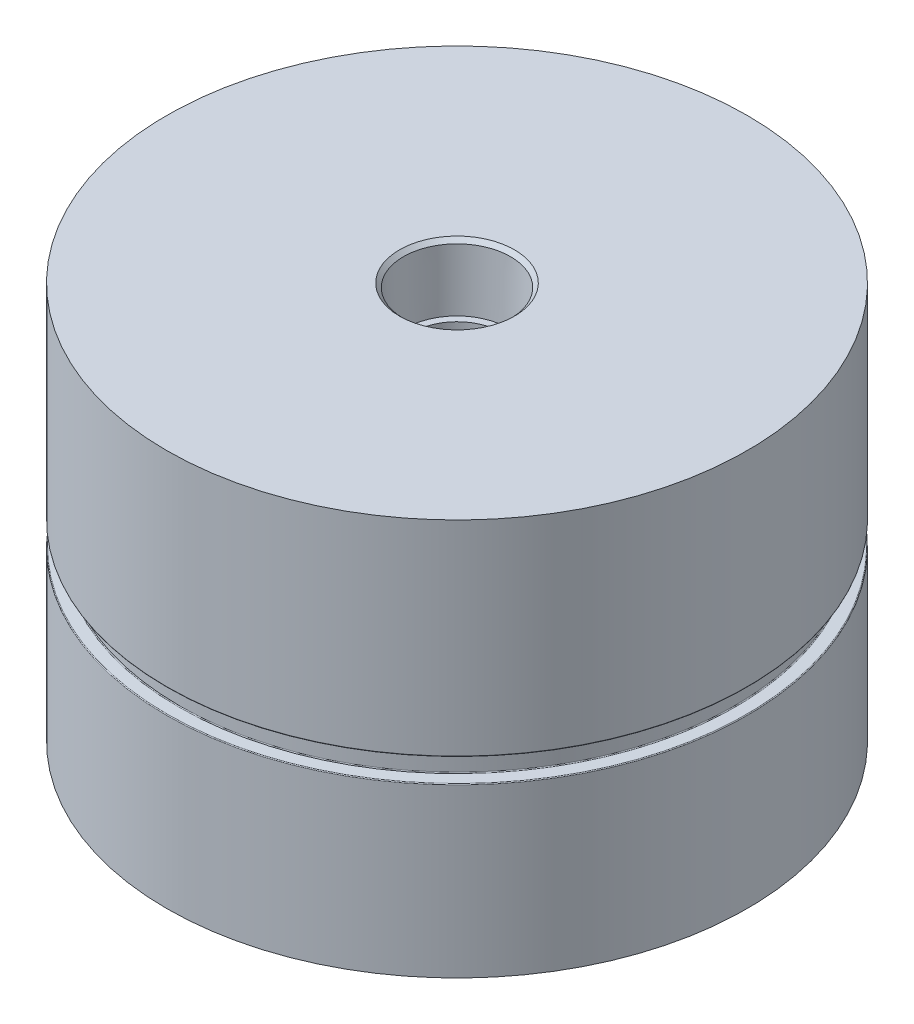
SolidWorks part; units mm, degrees
ref_plane "Front Plane" through (0, 0, 0) normal (0, 0, 1) x (1, 0, 0)
ref_plane "Top Plane" through (0, 0, 0) normal (0, 1, 0) x (1, 0, 0)
ref_plane "Right Plane" through (0, 0, 0) normal (1, 0, 0) x (0, 0, -1)
sketch "Sketch1" plane through (0, 0, 0) normal (0, 0, 1) x (1, 0, 0)
  line L0 (0, 32.1894) -> (0, -38.988) construction
  line L1 (0, -33.4044) -> (-46.4693, -33.4044)
  line L2 (-46.4693, -33.4044) -> (-46.4693, -6.5207)
  line L3 (-46.4693, -6.5207) -> (-44.4373, -6.4142)
  line L4 (-44.4373, -6.4142) -> (-44.4373, -2.8582)
  line L5 (-44.4373, -2.8582) -> (-46.4693, -2.7517)
  line L6 (-46.4693, -2.7517) -> (-46.4693, 30.0956)
  line L7 (-46.4693, 30.0956) -> (0, 30.0956)
  line L8 (0, 30.0956) -> (0, -33.4044)
  dimension "D1" = 92.9386
  dimension "D2" = 92.9386
  dimension "D3" = 88.8746
  dimension "D4" = 93
  dimension "D5" = 93
  dimension "D6" = 3.556
  dimension "D7" = 63.5
revolve "Revolve3" add sketch "Sketch1" angle 360 about L0
fillet "Fillet1" radius 0.127 2 edges at (0, -6.5207, 46.4693) (0, -2.7517, 46.4693)
fillet "Fillet2" radius 0.127 2 edges at (0, -2.8582, 44.4373) (0, -6.4142, 44.4373)
hole_wizard "3/8 NPT Tapped Hole2" positions "Sketch9" profile "Sketch10" size "3/8" standard "ANSI Inch" end condition through all
sketch "Sketch9" plane through (0, 30.0956, 0) normal (0, 1, 0) x (1, 0, 0)
  point P0 (0, 0)
sketch "Sketch10" plane through (0, 30.0956, 0) normal (1, 0, 0) x (0, 0, 1)
  line L0 (0, 0) -> (0, 63.5)
  line L1 (0, 63.5) -> (7.1374, 63.5)
  line L3 (7.1374, 63.5) -> (7.1374, 10.414)
  line L4 (7.1374, 10.414) -> (8.2697, 10.414)
  line L5 (8.2697, 10.414) -> (8.5751, 0.6324)
  line L6 (8.5751, 0.6324) -> (9.2075, 0)
  line L7 (9.2075, 0) -> (0, 0)
  line L8 (0, -6.35) -> (0, 107.95) construction
  line L9 (-8.5751, 0.6324) -> (-9.2075, 0) construction
  line L11 (-7.1374, 10.414) -> (-8.2697, 10.414) construction
  line L12 (-8.2697, 10.414) -> (-8.5751, 0.6324) construction
  dimension "Thru Tap Drill Dia." = 14.2748
  dimension "Thru Tap Drill Depth" = 63.5
  dimension "Thread Dia." = 17.1502
  dimension "Thread Angle" = 3.576
  dimension "Thread Depth" = 10.414
  dimension "Near C'Sink Dia." = 18.415
  dimension "Near C'Sink Angle" = 90
